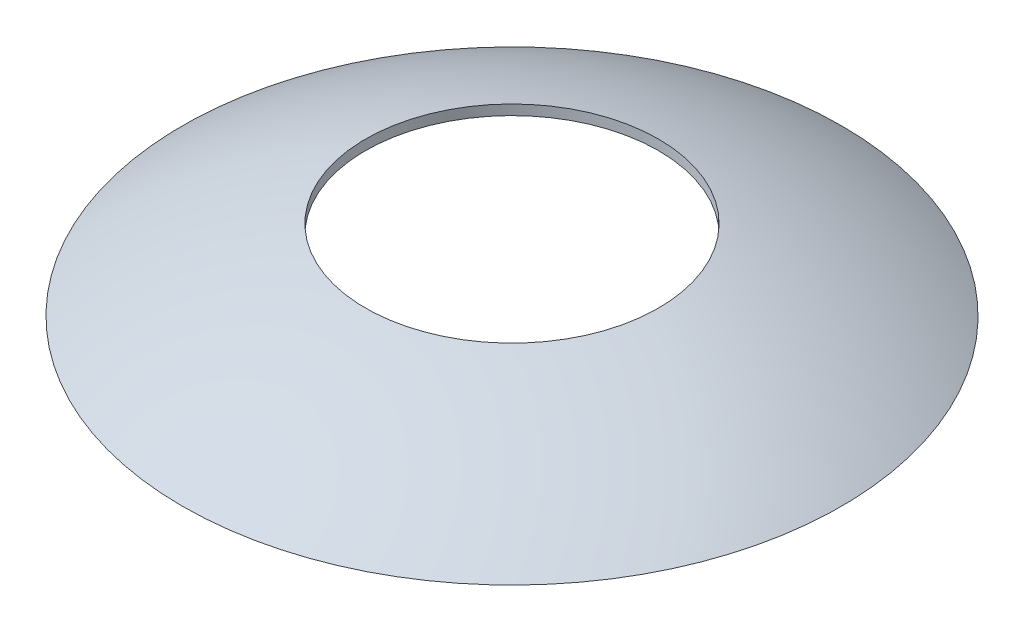
SolidWorks part; units mm, degrees
ref_plane "Front Plane" through (0, 0, 0) normal (0, 0, 1) x (1, 0, 0)
ref_plane "Top Plane" through (0, 0, 0) normal (0, 1, 0) x (1, 0, 0)
ref_plane "Right Plane" through (0, 0, 0) normal (1, 0, 0) x (0, 0, -1)
sketch "Sketch1" plane through (0, 0, 0) normal (0, 0, 1) x (1, 0, 0)
  line L0 (0, 0) -> (6.75, 0) construction
  line L1 (0, 0) -> (0, 2.1221) construction
  line L2 (0, 0) -> (3, 0) construction
  line L3 (3, 1.4336) -> (3, 1.6398)
  line L4 (6.75, 0) -> (6.3781, 0)
  line L5 (0.2, 0) -> (0.2, 1.7993) construction
  line L7 (0, 0) -> (0, 2) construction
  arc A0 (3, 1.6398) -> (6.75, 0) centre (0.0568, -10.199) cw
  arc A1 (3, 1.4336) -> (6.3781, 0) centre (0.0568, -10.199) cw
  arc A3 (0.2, 1.7993) -> (6.6403, -0.1672) centre (0.0568, -10.199) cw construction
  arc A4 (0, 2) -> (6.75, 0) centre (0.0568, -10.199) cw construction
  dimension "D1" = 6.75
  dimension "D3" = 3
  dimension "D4" = 0.2
revolve "Revolve1" add sketch "Sketch1" angle 360 about L1
sketch "Sketch2" plane through (0, 0, 0) normal (0, -1, 0) x (1, 0, 0)
  line L0 (-6.75, 0) -> (6.75, 0) construction
  circle A0 centre (0, 0) radius 6.75 construction
